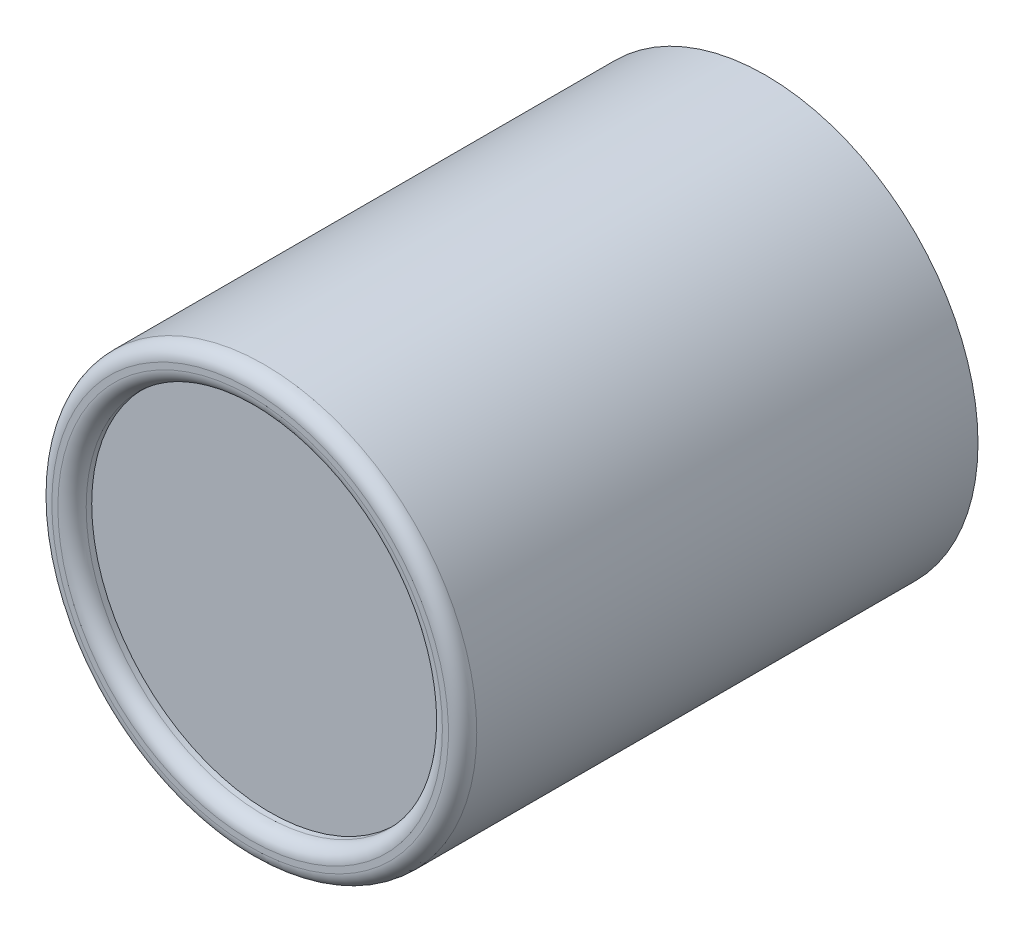
SolidWorks part; units mm, degrees
ref_plane "Front Plane" through (0, 0, 0) normal (0, 0, 1) x (1, 0, 0)
ref_plane "Top Plane" through (0, 0, 0) normal (0, 1, 0) x (1, 0, 0)
ref_plane "Right Plane" through (0, 0, 0) normal (1, 0, 0) x (0, 0, -1)
sketch "Sketch1" plane through (0, 0, 0) normal (0, 0, 1) x (1, 0, 0)
  circle A0 centre (0, 0) radius 0.75 construction
  dimension "D1" = 1.5
sketch "Sketch2" plane through (0, 0, 0) normal (1, 0, 0) x (0, 0, -1)
  line L0 (0, 0) -> (-0.9746, 0) construction
  line L1 (0, 0.75) -> (0, -0.75) construction
  line L2 (0, 0.75) -> (0, 0)
  line L3 (0, 0) -> (-0.75, 0)
  line L4 (0, 0.75) -> (-0.7695, 0.75)
  line L5 (-0.8195, 0.7) -> (-0.8195, 0.6788)
  line L6 (-0.7695, 0.6288) -> (-0.75, 0.6288)
  line L7 (-0.75, 0.6288) -> (-0.75, 0)
  arc A1 (-0.7695, 0.75) -> (-0.8195, 0.7) centre (-0.7695, 0.7) ccw
  arc A2 (-0.7695, 0.6288) -> (-0.8195, 0.6788) centre (-0.7695, 0.6788) cw
  dimension "D2" = 0.05
  dimension "D1" = 0.75
revolve "Revolve1" add sketch "Sketch2" angle 360 about L0
sketch "Sketch3" plane through (0, 0, 0) normal (0, 0, 1) x (1, 0, 0)
  circle A0 centre (0, 0) radius 0.75
extrude "Boss-Extrude1" add sketch "Sketch3" against normal blind 1
